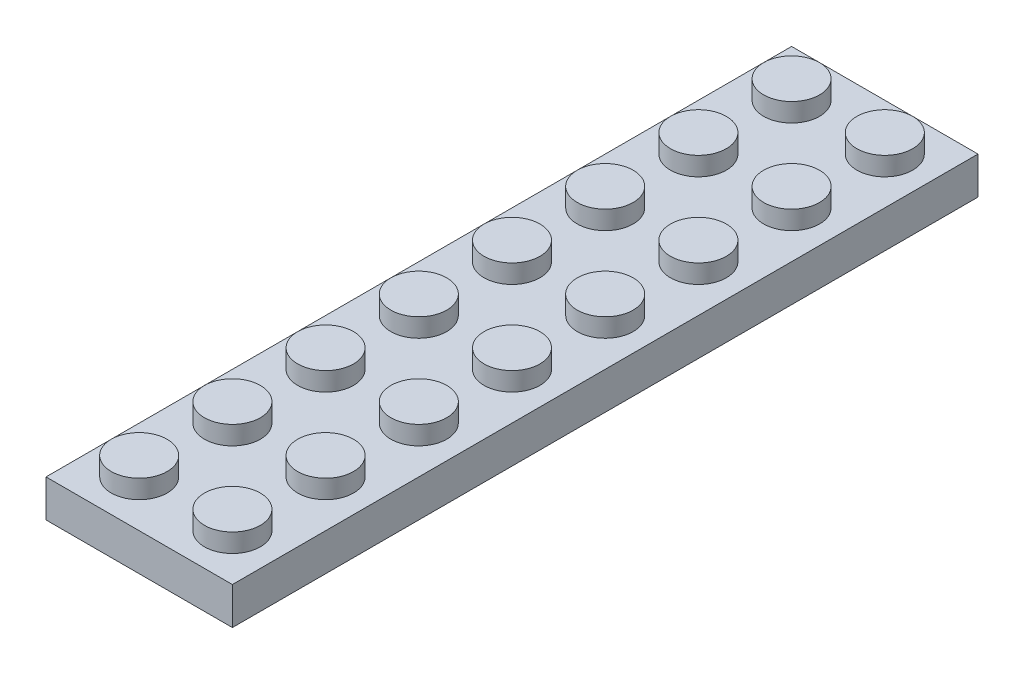
SolidWorks part; units mm, degrees
ref_plane "Front Plane" through (0, 0, 0) normal (0, 0, 1) x (1, 0, 0)
ref_plane "Top Plane" through (0, 0, 0) normal (0, 1, 0) x (1, 0, 0)
ref_plane "Right Plane" through (0, 0, 0) normal (1, 0, 0) x (0, 0, -1)
sketch "Sketch1" plane through (0, 0, 0) normal (0, 1, 0) x (1, 0, 0)
  line L1 (0, 0) -> (16, 0)
  line L2 (0, 0) -> (0, 64)
  line L3 (0, 64) -> (16, 64)
  line L4 (16, 0) -> (16, 64)
  dimension "D1" = 16
  dimension "D2" = 64
extrude "Boss-Extrude1" add sketch "Sketch1" along normal blind 3.2
sketch "Sketch2" plane through (0, 3.2, 0) normal (0, 1, 0) x (1, 0, 0)
  line L0 (8, 0) -> (8, 64) construction
  line L1 (0, 0) -> (16, 0) construction
  line L2 (16, 64) -> (0, 64) construction
  line L3 (16, 0) -> (16, 4) construction
  line L4 (16, 0) -> (16, 64) construction
  line L5 (16, 4) -> (12, 4) construction
  circle A0 centre (12, 4) radius 2.4
  dimension "D3" = 4.8
  dimension "D1" = 4
  dimension "D2" = 4
extrude "Boss-Extrude2" add sketch "Sketch2" along normal blind 1.6
pattern_linear "LPattern1" count 2 spacing 8 along (-1, 0, 0) count 8 spacing 8 along (0, 0, -1) of "Boss-Extrude2"
shell "Shell1" thickness 1.6
